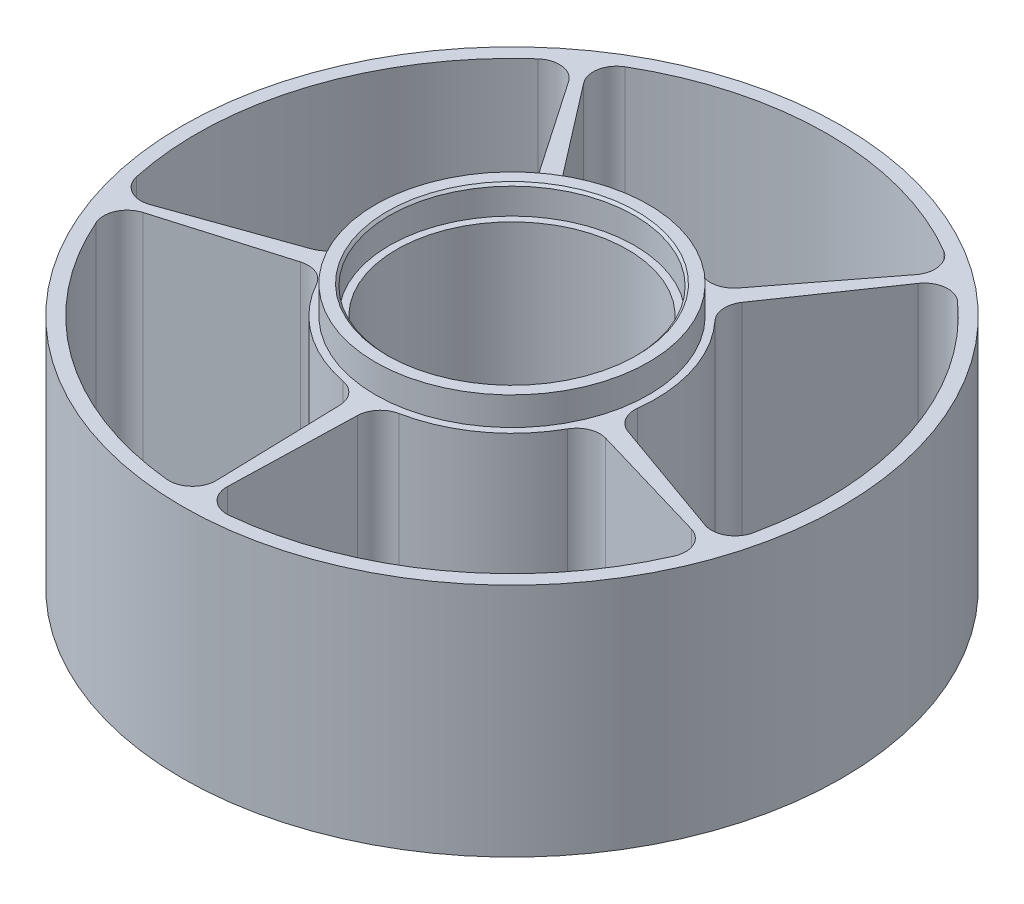
SolidWorks part; units mm, degrees
material "6061-T6 (SS)"
ref_plane "前视基准面" through (0, 0, 0) normal (0, 0, 1) x (1, 0, 0)
ref_plane "上视基准面" through (0, 0, 0) normal (0, 1, 0) x (1, 0, 0)
ref_plane "右视基准面" through (0, 0, 0) normal (1, 0, 0) x (0, 0, -1)
sketch "草图1" plane through (0, 0, 0) normal (0, 0, 1) x (1, 0, 0)
  line L0 (0, 82.6595) -> (0, -77.2474) construction
  line L1 (24.5, 0) -> (30.5, 0)
  line L2 (70, 0) -> (70, 50)
  line L3 (0, 3) -> (0, 0)
  line L4 (67, 0) -> (67, 50)
  line L6 (-49.4787, 0) -> (70, 0) construction
  line L7 (-46.4787, 3) -> (-46.4787, 54.9999) construction
  line L8 (-49.4787, 0) -> (-49.4787, 54.9999) construction
  line L9 (-46.4787, 3) -> (67, 3) construction
  line L10 (67, 50) -> (70, 50)
  line L12 (30.5, 50) -> (24.5, 50)
  line L13 (24.5, 50) -> (24.5, 0)
  line L14 (67, 3) -> (67, 50) construction
  line L15 (30.5, 50) -> (30.5, 0)
  line L16 (67, 0) -> (70, 0)
  point P8 (0, 0)
  point P16 (91.7812, -2.7173)
  point P18 (20, 47)
  dimension "D1" = 3
  dimension "D2" = 140
  dimension "D3" = 50
  dimension "D4" = 49
  dimension "D6" = 61
revolve "旋转1" add sketch "草图1" angle 360 about L0
sketch "草图2" plane through (0, 0, 0) normal (0, -1, 0) x (1, 0, 0)
  line L0 (0, -95.9599) -> (0, 103.8492) construction
  line L1 (110.3654, 0) -> (-108.2226, 0) construction
  point P5 (0, -27.5)
  point P6 (0, 27.5)
  point P7 (19.4454, 19.4454)
  point P8 (27.5, 0)
  point P9 (-19.4454, -19.4454)
  point P10 (-27.5, 0)
  point P11 (-19.4454, 19.4454)
  point P12 (0, 0)
  point P13 (19.4454, -19.4454)
  dimension "D1" = 55
  dimension "D2" = 8
hole_wizard "M4 螺纹孔1" positions "草图3" profile "草图4" tap size "M4" standard "GB"
sketch "草图3" plane through (0, 0, 0) normal (0, -1, 0) x (-1, 0, 0)
  point P0 (0, 27.5)
  point P3 (19.4454, -19.4454)
  point P6 (27.5, 0)
  point P9 (19.4454, 19.4454)
  point P12 (0, -27.5)
  point P15 (-19.4454, -19.4454)
  point P18 (-27.5, 0)
  point P21 (-19.4454, 19.4454)
cosmetic thread "孔螺蚊线5" parameters "D1"=10, "D2"=4
cosmetic thread "孔螺蚊线6" parameters "D1"=10, "D2"=4
cosmetic thread "孔螺蚊线7" parameters "D1"=10, "D2"=4
cosmetic thread "孔螺蚊线8" parameters "D1"=10, "D2"=4
sketch "草图4" plane through (0, 0, -27.5) normal (1, 0, 0) x (0, 0, -1)
  line L0 (0, 0) -> (0, 10.9914)
  line L1 (0, 10.9914) -> (1.65, 10)
  line L2 (1.65, 10) -> (1.65, 0)
  line L5 (1.65, 0) -> (0, 0)
  line L10 (0, 10.9914) -> (-1.65, 10) construction
  line L11 (0, -6.35) -> (0, 107.95) construction
  dimension "螺纹孔钻头直径" = 3.3
  dimension "螺纹孔钻头深度" = 10
  dimension "导头角度" = 118
cosmetic thread "孔螺蚊线9" parameters "D1"=10, "D2"=4
cosmetic thread "孔螺蚊线10" parameters "D1"=10, "D2"=4
cosmetic thread "孔螺蚊线11" parameters "D1"=10, "D2"=4
cosmetic thread "孔螺蚊线12" parameters "D1"=10, "D2"=4
sketch "草图5" plane through (0, 50, 0) normal (0, 1, 0) x (1, 0, 0)
  line L0 (0, -103.0392) -> (0, 91.1604) construction
  line L1 (106.828, 0) -> (-101.6325, 0) construction
  line L14 (2, -30.4344) -> (1, -66.9925)
  line L15 (-2, -30.4344) -> (-1, -66.9925)
  line L16 (-29.5628, -7.5026) -> (-64.0227, -19.7508)
  line L17 (-28.3268, -11.3068) -> (-63.4047, -21.6529)
  line L18 (-16.2708, 25.7975) -> (-38.5682, 54.7859)
  line L19 (-19.5069, 23.4463) -> (-40.1862, 53.6103)
  line L20 (19.5069, 23.4463) -> (40.1862, 53.6103)
  line L21 (16.2708, 25.7975) -> (38.5682, 54.7859)
  line L22 (28.3268, -11.3068) -> (63.4047, -21.6529)
  line L23 (29.5628, -7.5026) -> (64.0227, -19.7508)
  arc A19 (-2, -30.4344) -> (2, -30.4344) centre (0, 0) ccw
  circle A21 centre (0, 0) radius 30.5 construction
  arc A24 (-1, -66.9925) -> (1, -66.9925) centre (0, 0) ccw
  circle A25 centre (0, 0) radius 67 construction
  arc A26 (-64.0227, -19.7508) -> (-63.4047, -21.6529) centre (0, 0) ccw
  arc A27 (-29.5628, -7.5026) -> (-28.3268, -11.3068) centre (0, 0) ccw
  arc A28 (-38.5682, 54.7859) -> (-40.1862, 53.6103) centre (0, 0) ccw
  arc A29 (-16.2708, 25.7975) -> (-19.5069, 23.4463) centre (0, 0) ccw
  arc A30 (40.1862, 53.6103) -> (38.5682, 54.7859) centre (0, 0) ccw
  arc A31 (19.5069, 23.4463) -> (16.2708, 25.7975) centre (0, 0) ccw
  arc A32 (63.4047, -21.6529) -> (64.0227, -19.7508) centre (0, 0) ccw
  arc A33 (28.3268, -11.3068) -> (29.5628, -7.5026) centre (0, 0) ccw
  point P32 (0, 0)
  dimension "D1" = 4
  dimension "D2" = 2
extrude "凸台-拉伸1" add sketch "草图5" against normal up to surface (50 mm away) up to face at (0, 0, -29.15)
sketch "草图7" plane through (0, 50, 0) normal (0, 1, 0) x (1, 0, 0)
  circle A0 centre (0, 0) radius 26
  circle A1 centre (0, 0) radius 29
  dimension "D1" = 52
  dimension "D2" = 3
extrude "凸台-拉伸3" add sketch "草图7" along normal blind 6
chamfer "倒角1" distance 0.5 angle 45 2 edges at (0, 56, 26) (0, 0, 24.5)
fillet "圆角1" radius 5 20 edges at (-1, 25, 66.9925) (-2, 25, 30.4344) (-28.3268, 25, 11.3068) (-63.4047, 25, 21.6529) (-19.5069, 25, -23.4463) (-29.5628, 25, 7.5026) (-64.0227, 25, 19.7508) (-40.1862, 25, -53.6103) (16.2708, 25, -25.7975) (-16.2708, 25, -25.7975) (-38.5682, 25, -54.7859) (38.5682, 25, -54.7859) (29.5628, 25, 7.5026) (19.5069, 25, -23.4463) (40.1862, 25, -53.6103) (64.0227, 25, 19.7508) (1, 25, 66.9925) (2, 25, 30.4344) (28.3268, 25, 11.3068) (63.4047, 25, 21.6529)
move or copy body "实体-移动/复制1" [suppressed] bodies to move or copy 113
